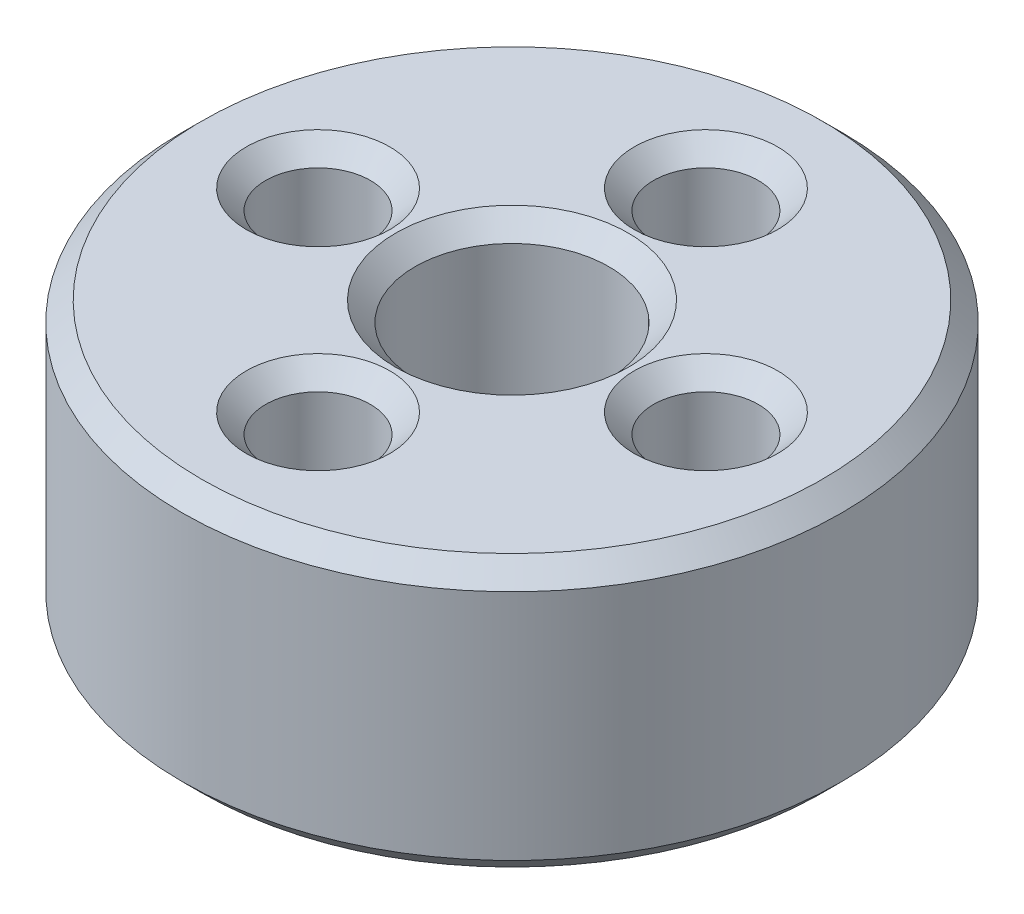
SolidWorks part; units mm, degrees
ref_plane "前视基准面" through (0, 0, 0) normal (0, 0, 1) x (1, 0, 0)
ref_plane "上视基准面" through (0, 0, 0) normal (0, 1, 0) x (1, 0, 0)
ref_plane "右视基准面" through (0, 0, 0) normal (1, 0, 0) x (0, 0, -1)
sketch "草图1" plane through (0, 0, 0) normal (0, 1, 0) x (1, 0, 0)
  line L0 (0, 0) -> (-5.9584, 0) construction
  circle A1 centre (0, 0) radius 8.5
  circle A6 centre (0, 0) radius 5 construction
  circle A7 centre (-5, 0) radius 1.35
  circle A8 centre (0, 5) radius 1.35
  circle A9 centre (5, 0) radius 1.35
  circle A10 centre (0, -5) radius 1.35
  circle A12 centre (0, 0) radius 2.5
  point P15 (0, 0)
  point P25 (0, 0)
  point P61 (0, 0)
  dimension "D2" = 17
  dimension "D6" = 10
  dimension "D7" = 2.7
  dimension "D9" = 5
extrude "凸台-拉伸1" add sketch "草图1" along normal blind 7
chamfer "倒角1" distance 0.5 angle 45 12 edges at (0, 0, 6.35) (5, 0, 1.35) (0, 0, -3.65) (0, 0, 2.5) (-5, 0, 1.35) (0, 0, 8.5) (0, 7, 6.35) (0, 7, -3.65) (-5, 7, 1.35) (0, 7, 8.5) (0, 7, 2.5) (5, 7, 1.35)
